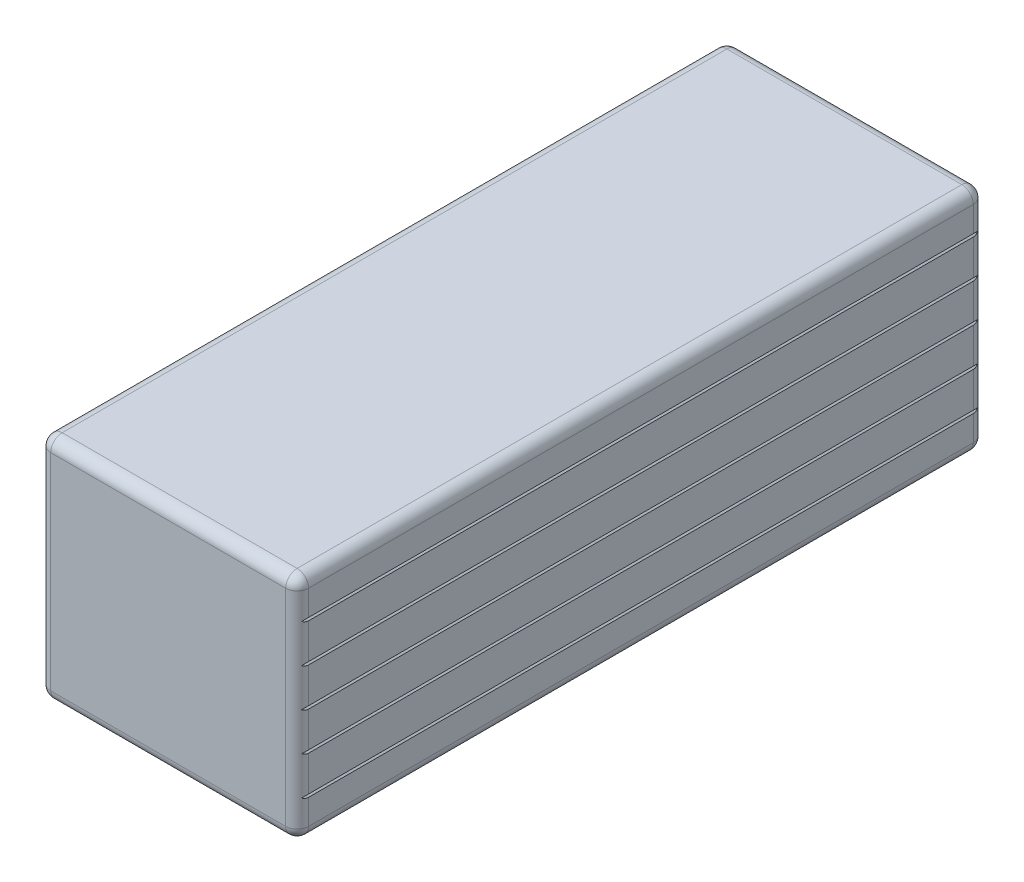
SolidWorks part; units mm, degrees
ref_plane "Front Plane" through (0, 0, 0) normal (0, 0, 1) x (1, 0, 0)
ref_plane "Top Plane" through (0, 0, 0) normal (0, 1, 0) x (1, 0, 0)
ref_plane "Right Plane" through (0, 0, 0) normal (1, 0, 0) x (0, 0, -1)
sketch "Sketch1" plane through (0, 0, 0) normal (0, 0, 1) x (1, 0, 0)
  line L1 (-22.5, 20) -> (22.5, 20)
  line L2 (-22.5, 20) -> (-22.5, -20)
  line L3 (-22.5, -20) -> (22.5, -20)
  line L4 (22.5, 20) -> (22.5, -20)
  dimension "D1" = 45
  dimension "D2" = 40
  dimension "D3" = 20
  dimension "D4" = 22.5
extrude "Boss-Extrude1" add sketch "Sketch1" against normal blind 120
fillet "Fillet1" radius 2 12 edges at (0, -20, -120) (-22.5, -20, -60) (-22.5, 0, -120) (-22.5, 20, -60) (0, 20, -120) (22.5, 20, -60) (22.5, 0, -120) (22.5, -20, -60) (0, 20, 0) (22.5, 0, 0) (0, -20, 0) (-22.5, 0, 0)
sketch "Sketch2" plane through (0, 0, 0) normal (0, 0, 1) x (1, 0, 0)
  line L0 (22.5, 13.58) -> (22.25, 13.33)
  line L1 (22.5, 18) -> (22.5, -18) construction
  line L2 (22.25, 13.33) -> (22.5, 13.08)
  line L3 (-20.5, 20) -> (20.5, 20) construction
  line L4 (22.5, 13.58) -> (22.5, 13.08)
  line L5 (-22.5, 13.58) -> (-22.25, 13.33)
  line L6 (-22.5, -18) -> (-22.5, 18) construction
  line L7 (-22.25, 13.33) -> (-22.5, 13.08)
  line L8 (-22.5, 13.08) -> (-22.5, 13.58)
  dimension "D1" = 0.5
  dimension "D2" = 6.67
  dimension "D3" = 0.5
  dimension "D4" = 6.67
extrude "Cut-Extrude1" cut sketch "Sketch2" against normal through all both and the other way through all
pattern_linear "LPattern1" count 5 spacing 6.67 along (0, -1, 0) of "Cut-Extrude1"
